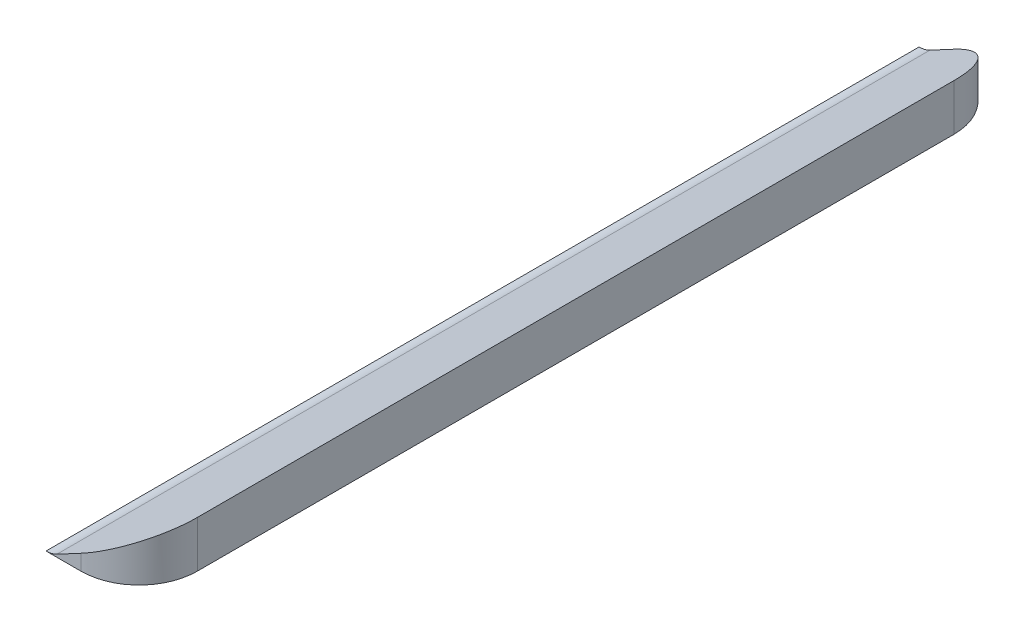
SolidWorks part; units mm, degrees
ref_plane "Front Plane" through (0, 0, 0) normal (0, 0, 1) x (1, 0, 0)
ref_plane "Top Plane" through (0, 0, 0) normal (0, 1, 0) x (1, 0, 0)
ref_plane "Right Plane" through (0, 0, 0) normal (1, 0, 0) x (0, 0, -1)
sketch "Sketch1" plane through (0, 0, 0) normal (0, 1, 0) x (1, 0, 0)
  line L1 (0, 0) -> (40, 0)
  line L2 (0, 0) -> (0, 200)
  line L3 (0, 200) -> (40, 200)
  line L4 (40, 0) -> (40, 200)
  dimension "D1" = 40
  dimension "D2" = 200
extrude "Boss-Extrude1" add sketch "Sketch1" along normal blind 10
sketch "Sketch2" plane through (0, 10, 0) normal (0, 1, 0) x (1, 0, 0)
  line L0 (0, 0) -> (40, 0) construction
  line L1 (12.5, 175) -> (27.5, 175)
  line L2 (12.5, 175) -> (12.5, 25)
  line L3 (12.5, 25) -> (27.5, 25)
  line L4 (27.5, 175) -> (27.5, 25)
  line L5 (12.5, 175) -> (27.5, 25) construction
  line L6 (12.5, 25) -> (27.5, 175) construction
  line L7 (40, 0) -> (40, 200) construction
  point P0 (20, 100)
  point P7 (20, 0)
  point P10 (40, 100)
  dimension "D1" = 150
  dimension "D2" = 15
extrude "Boss-Extrude2" add sketch "Sketch2" along normal blind 8
fillet "Fillet1" radius 10 2 edges at (27.5, 14, -175) (27.5, 14, -25)
sketch "Sketch3" plane through (0, 0, 0) normal (0, 0, 1) x (1, 0, 0)
  line L0 (27.5, 18) -> (12.5, 18)
  line L1 (12.5, 18) -> (12.5, 10)
  line L2 (12.5, 10) -> (27.5, 18)
extrude "Cut-Extrude1" cut sketch "Sketch3" against normal through all
fillet "Fillet2" radius 4 1 edges at (12.5, 10, -100)
sketch "Sketch4" plane through (0, 0, 0) normal (0, 0, 1) x (1, 0, 0)
  line L0 (0, 10) -> (40, 10) construction
  line L1 (0, 10) -> (40, 10)
split "Split1" trim tools "Sketch4" bodies to split 103 resulting bodies 104
sketch "Orientation Sketch" plane through (0, 10, 0) normal (0, -1, 0) x (-1, 0, 0)
  line L0 (-17.5, 175) -> (-11.5, 175) construction
  line L1 (-27.5, 35) -> (-27.5, 165) construction
  line L2 (-11.5, 25) -> (-17.5, 25) construction
  line L3 (-11.5, 25) -> (-11.5, 175) construction
  line L4 (-17.5, 175) -> (-11.5, 175)
  line L5 (-27.5, 35) -> (-27.5, 165)
  line L6 (-11.5, 25) -> (-17.5, 25)
  line L7 (-11.5, 25) -> (-11.5, 175)
  arc A0 (-17.5, 175) -> (-27.5, 165) centre (-17.5, 165) ccw construction
  arc A1 (-27.5, 35) -> (-17.5, 25) centre (-17.5, 35) ccw construction
  arc A2 (-17.5, 175) -> (-27.5, 165) centre (-17.5, 165) ccw
  arc A3 (-27.5, 35) -> (-17.5, 25) centre (-17.5, 35) ccw
  point P8 (-19.5, 100)
other "FormTool1"
